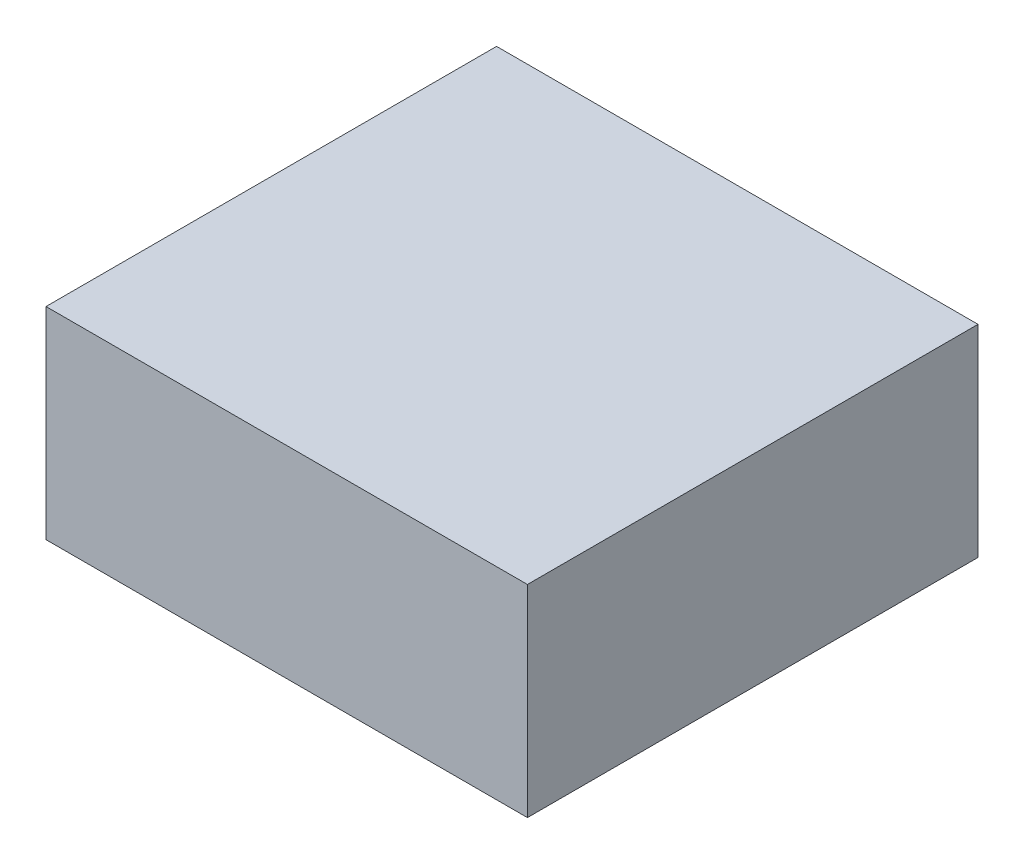
SolidWorks part; units mm, degrees
ref_plane "Front Plane" through (0, 0, 0) normal (0, 0, 1) x (1, 0, 0)
ref_plane "Top Plane" through (0, 0, 0) normal (0, 1, 0) x (1, 0, 0)
ref_plane "Right Plane" through (0, 0, 0) normal (1, 0, 0) x (0, 0, -1)
sketch "Sketch1" plane through (0, 0, 0) normal (0, 1, 0) x (1, 0, 0)
  line L0 (24.15, 22.5) -> (9.95, 22.5)
  line L1 (-24.15, -22.5) -> (24.15, -22.5)
  line L2 (-24.15, -22.5) -> (-24.15, 22.5)
  line L3 (-24.15, 22.5) -> (24.15, 22.5)
  line L4 (24.15, -22.5) -> (24.15, 22.5)
  line L5 (-24.15, -22.5) -> (24.15, 22.5) construction
  line L6 (-24.15, 22.5) -> (24.15, -22.5) construction
  line L7 (9.95, 22.5) -> (0.95, 22.5)
  line L17 (25.75, 24.1) -> (-25.75, 24.1)
  line L18 (25.75, 24.1) -> (25.75, -24.1)
  line L19 (25.75, -24.1) -> (-25.75, -24.1)
  line L20 (-25.75, 24.1) -> (-25.75, -24.1)
  point P0 (0, 0)
  dimension "D1" = 45
  dimension "D2" = 48.3
  dimension "D3" = 14.2
  dimension "D4" = 9
extrude "Boss-Extrude1" add sketch "Sketch1" along normal blind 21.6 contours L17 L20 L19 L18 L4 L1 L2 L3 L0 | L1 L4 L0 L3 L2
